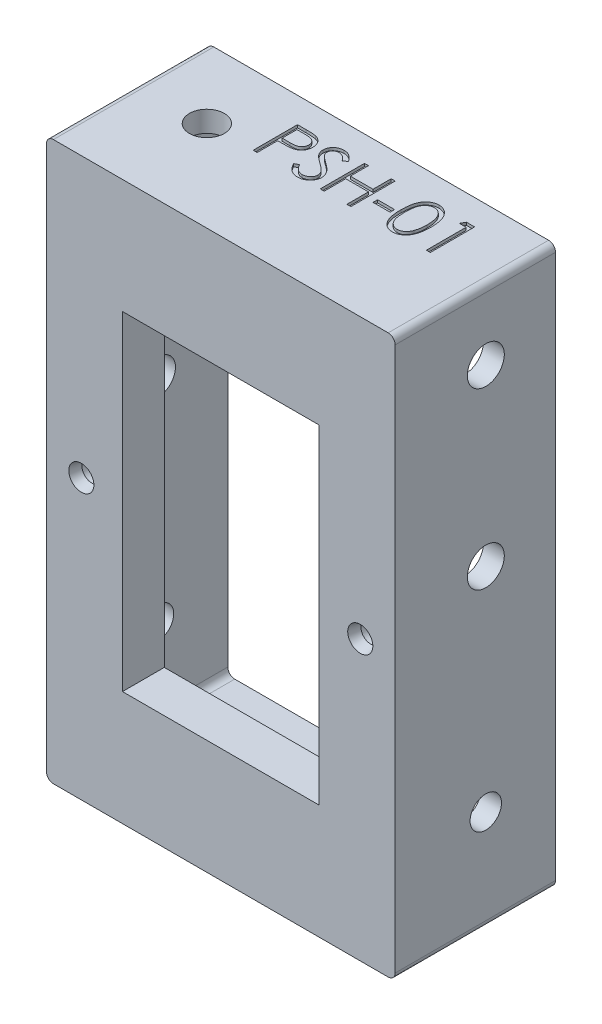
SolidWorks part; units mm, degrees
ref_plane "Front" through (0, 0, 0) normal (0, 0, 1) x (1, 0, 0)
ref_plane "Top" through (0, 0, 0) normal (0, 1, 0) x (1, 0, 0)
ref_plane "Right" through (0, 0, 0) normal (1, 0, 0) x (0, 0, -1)
sketch "Sketch3" plane through (0, 0, 0) normal (0, 0, 1) x (1, 0, 0)
  line L0 (10.9, 16.4) -> (0, 16.4) construction
  line L1 (0, 0) -> (50, 0)
  line L2 (0, 0) -> (0, 80)
  line L3 (0, 80) -> (50, 80)
  line L4 (50, 0) -> (50, 80)
  line L5 (10.9, 16.4) -> (39.1, 16.4)
  line L6 (10.9, 16.4) -> (10.9, 63.6)
  line L7 (10.9, 63.6) -> (39.1, 63.6)
  line L8 (39.1, 16.4) -> (39.1, 63.6)
  line L9 (39.1, 16.4) -> (50, 16.4) construction
  line L10 (10.9, 16.4) -> (10.9, 0) construction
  line L11 (10.9, 63.6) -> (10.9, 80) construction
  line L12 (25, 63.6) -> (25, 40) construction
  line L13 (25, 40) -> (25, 16.4) construction
  line L14 (25, 40) -> (5, 40) construction
  line L15 (25, 40) -> (45, 40) construction
  circle A0 centre (5, 40) radius 1.4
  circle A1 centre (45, 40) radius 1.4
  dimension "D5" = 40
  dimension "D6" = 2.8
  dimension "D1" = 50
  dimension "D2" = 80
  dimension "D3" = 28.2
  dimension "D4" = 47.2
extrude "Boss-Extrude1" add sketch "Sketch3" along normal blind 23
sketch "Sketch4" plane through (0, 0, 0) normal (0, 0, -1) x (-1, 0, 0)
  line L8 (-47, 3) -> (-3, 3)
  line L9 (-3, 3) -> (-3, 77)
  line L10 (-47, 77) -> (-47, 3)
  line L11 (-3, 77) -> (-47, 77)
  line L12 (-47, 3) -> (-3, 3)
  line L13 (-3, 3) -> (-3, 77)
  line L14 (-47, 77) -> (-47, 3)
  line L15 (-3, 77) -> (-47, 77)
  dimension "D1" = 3
extrude "Cut-Extrude1" cut sketch "Sketch4" against normal offset from surface (17 mm away) 6 up to face at (25, 40, 23)
chamfer "Chamfer1" distance 0.4 angle 75 2 edges at (46.4, 40, 23) (6.4, 40, 23)
fillet "Fillet1" radius 1 4 edges at (0, 0, 11.5) (50, 0, 11.5) (50, 80, 11.5) (0, 80, 11.5)
fillet "Fillet2" radius 1 4 edges at (47, 3, 8.5) (3, 3, 8.5) (3, 77, 8.5) (47, 77, 8.5)
sketch "Sketch5" plane through (0, 0, 0) normal (-1, 0, 0) x (0, 0, 1)
  line L0 (0, 79) -> (0, 1) construction
  line L1 (0, 80) -> (23, 80) construction
  line L2 (10, 70) -> (10, 45) construction
  line L3 (10, 45) -> (10, 14.5) construction
  circle A0 centre (10, 70) radius 2.5
  circle A1 centre (10, 45) radius 2.5
  circle A2 centre (10, 14.5) radius 2.25
  dimension "D1" = 10
  dimension "D2" = 5
  dimension "D3" = 10
  dimension "D4" = 25
  dimension "D5" = 14.5
  dimension "D6" = 4.5
extrude "Cut-Extrude2" cut sketch "Sketch5" against normal up to next
hole_wizard "M5 Clearance Hole1" positions "Sketch6" profile "Sketch7" hole size "M5" standard "ANSI Metric"
sketch "Sketch6" plane through (47, 0, 0) normal (-1, 0, 0) x (0, 0, 1)
  point P0 (10, 70)
  point P4 (10, 45)
sketch "Sketch7" plane through (47, 70, 10) normal (0, 1, 0) x (0, 0, 1)
  line L0 (0, 0) -> (0, 3)
  line L1 (0, 3) -> (2.65, 3)
  line L2 (2.65, 3) -> (2.65, 0)
  line L5 (2.65, 0) -> (0, 0)
  line L11 (0, -6.35) -> (0, 107.95) construction
  dimension "Thru Hole Dia." = 5.3
  dimension "Thru Hole Depth" = 3
sketch "Sketch8" plane through (0, 80, 0) normal (0, 1, 0) x (1, 0, 0)
  line L0 (49, 0) -> (1, 0) construction
  line L1 (0, -23) -> (0, 0) construction
  circle A0 centre (10, -10) radius 2.5
  dimension "D1" = 5
  dimension "D3" = 10
  dimension "D2" = 10
extrude "Cut-Extrude3" cut sketch "Sketch8" against normal up to next
hole_wizard "M5 Clearance Hole2" positions "Sketch10" profile "Sketch11" hole size "M5" standard "ANSI Metric"
sketch "Sketch10" plane through (0, 3, 0) normal (0, 1, 0) x (1, 0, 0)
  point P0 (10, -10)
sketch "Sketch11" plane through (10, 3, 10) normal (1, 0, 0) x (0, 0, 1)
  line L0 (0, 0) -> (0, 3)
  line L1 (0, 3) -> (2.65, 3)
  line L2 (2.65, 3) -> (2.65, 0)
  line L5 (2.65, 0) -> (0, 0)
  line L11 (0, -6.35) -> (0, 107.95) construction
  dimension "Thru Hole Dia." = 5.3
  dimension "Thru Hole Depth" = 3
sketch "Sketch12" plane through (47, 0, 0) normal (-1, 0, 0) x (0, 0, 1)
  circle A0 centre (10, 14.5) radius 2.25 construction
  circle A1 centre (10, 14.5) radius 2.25
extrude "Cut-Extrude4" cut sketch "Sketch12" against normal through all
sketch "Sketch13" plane through (0, 80, 0) normal (0, 1, 0) x (1, 0, 0)
  line L0 (10, -10) -> (50, -10) construction
  line L1 (50, 0) -> (50, -23) construction
  text T0 "PSH-01"
extrude "Cut-Extrude5" cut sketch "Sketch13" against normal blind 0.4
sketch "Sketch14" plane through (0, 0, 23) normal (0, 0, 1) x (1, 0, 0)
  line L1 (10.25, 68.5) -> (39.75, 68.5)
  line L2 (10.25, 68.5) -> (10.25, 11.5)
  line L3 (10.25, 11.5) -> (39.75, 11.5)
  line L4 (39.75, 68.5) -> (39.75, 11.5)
  line L6 (25, 68.5) -> (25, 63.6) construction
  line L7 (39.1, 63.6) -> (10.9, 63.6) construction
  line L8 (25, 11.5) -> (25, 16.4) construction
  line L9 (10.9, 16.4) -> (39.1, 16.4) construction
  dimension "D1" = 57
  dimension "D2" = 29.5
extrude "Cut-Extrude6" [suppressed] cut sketch "Sketch14" against normal through all
